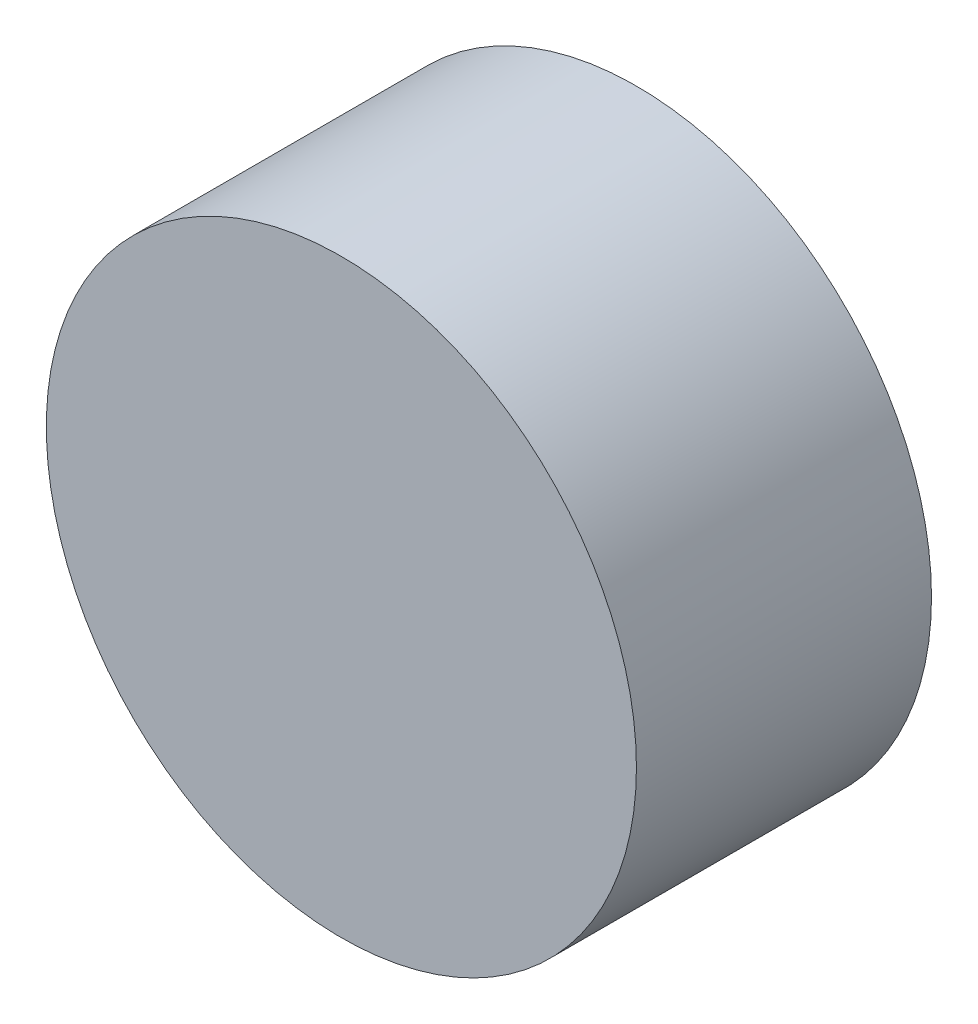
SolidWorks part; units mm, degrees
ref_plane "Front" through (0, 0, 0) normal (0, 0, 1) x (1, 0, 0)
ref_plane "Top" through (0, 0, 0) normal (0, 1, 0) x (1, 0, 0)
ref_plane "Right" through (0, 0, 0) normal (1, 0, 0) x (0, 0, -1)
sketch "Sketch1" plane through (0, 0, 0) normal (0, 0, 1) x (1, 0, 0)
  circle A0 centre (0, 0) radius 100
  dimension "D1" = 200
extrude "Boss-Extrude1" add sketch "Sketch1" along normal blind 100
